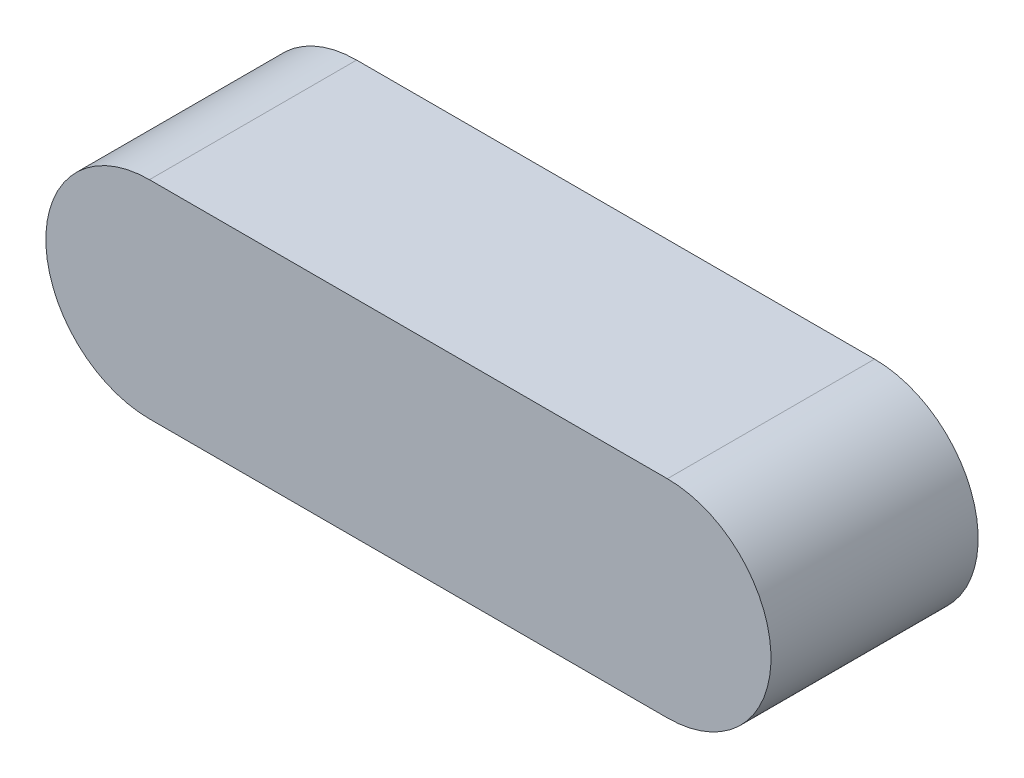
SolidWorks part; units mm, degrees
ref_plane "正面" through (0, 0, 0) normal (0, 0, 1) x (1, 0, 0)
ref_plane "平面" through (0, 0, 0) normal (0, 1, 0) x (1, 0, 0)
ref_plane "右側面" through (0, 0, 0) normal (1, 0, 0) x (0, 0, -1)
sketch "ｽｹｯﾁ1" plane through (0, 0, 0) normal (0, 0, 1) x (1, 0, 0)
  line L0 (0, 0) -> (10, 0) construction
  line L1 (0, 2) -> (10, 2)
  line L2 (0, -2) -> (10, -2)
  arc A0 (0, 2) -> (0, -2) centre (0, 0) ccw
  arc A1 (10, -2) -> (10, 2) centre (10, 0) ccw
  point P3 (5, 0)
  dimension "D2" = 2
  dimension "D1" = 10
extrude "ﾎﾞｽ - 押し出し1" add sketch "ｽｹｯﾁ1" along normal blind 4
